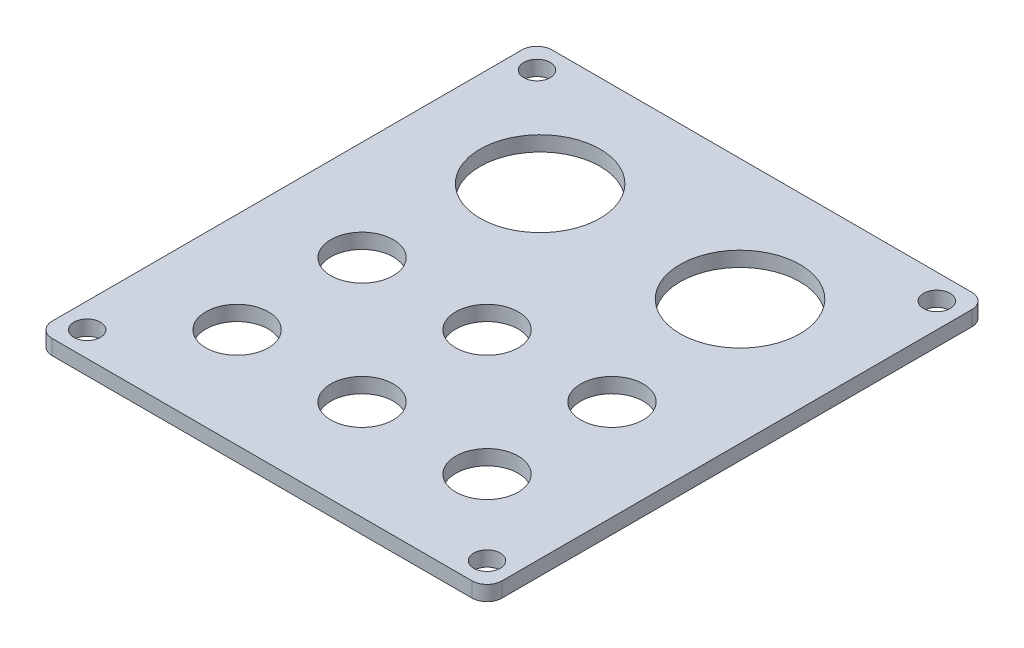
SolidWorks part; units mm, degrees
ref_plane "Front Plane" through (0, 0, 0) normal (0, 0, 1) x (1, 0, 0)
ref_plane "Top Plane" through (0, 0, 0) normal (0, 1, 0) x (1, 0, 0)
ref_plane "Right Plane" through (0, 0, 0) normal (1, 0, 0) x (0, 0, -1)
sketch "Sketch1" plane through (0, 0, 0) normal (0, 1, 0) x (1, 0, 0)
  line L1 (0, 0) -> (90, 0)
  line L2 (0, 0) -> (0, 100)
  line L3 (0, 100) -> (90, 100)
  line L4 (90, 0) -> (90, 100)
  dimension "D1" = 100
  dimension "D2" = 90
extrude "Boss-Extrude1" add sketch "Sketch1" along normal blind 3
sketch "Sketch2" plane through (0, 3, 0) normal (0, 1, 0) x (1, 0, 0)
  line L0 (0, 100) -> (0, 0) construction
  line L1 (0, 0) -> (90, 0) construction
  circle A0 centre (20, 20) radius 6.25
  dimension "D1" = 12.5
  dimension "D2" = 20
  dimension "D3" = 20
extrude "Cut-Extrude1" cut sketch "Sketch2" against normal up to surface (3 mm away) up to face at (45, 0, -50)
pattern_linear "LPattern1" count 3 spacing 25 along (1, 0, 0) count 2 spacing 25 along (0, 0, -1) of "Cut-Extrude1"
sketch "Sketch3" plane through (0, 3, 0) normal (0, 1, 0) x (1, 0, 0)
  line L0 (65, 75.625) -> (25, 75.625) construction
  line L1 (90, 100) -> (0, 100) construction
  line L2 (20, 51.25) -> (20, 100) construction
  circle A0 centre (25, 75.625) radius 12
  circle A1 centre (65, 75.625) radius 12
  circle A2 centre (20, 45) radius 6.25 construction
  circle A3 centre (25, 75.625) radius 14 construction
  circle A4 centre (65, 75.625) radius 14 construction
  point P3 (45, 75.625)
  point P5 (45, 100)
  point P13 (20, 75.625)
  dimension "D1" = 24
  dimension "D3" = 28
  dimension "D2" = 40
extrude "Cut-Extrude2" cut sketch "Sketch3" against normal up to surface (3 mm away) up to face at (45, 0, -26.25)
hole_wizard "M5 Clearance Hole1" positions "Sketch4" profile "Sketch5" hole size "M5" standard "ANSI Metric" end condition up to next
sketch "Sketch4" plane through (0, 3, 0) normal (0, 1, 0) x (1, 0, 0)
  line L18 (5, 95) -> (5, 5)
  line L19 (5, 5) -> (85, 5)
  line L20 (85, 5) -> (85, 95)
  line L21 (85, 95) -> (5, 95)
  line L22 (5, 95) -> (5, 5)
  line L23 (5, 5) -> (85, 5)
  line L24 (85, 5) -> (85, 95)
  line L25 (85, 95) -> (5, 95)
  point P135 (5, 95)
  point P136 (5, 5)
  point P137 (85, 5)
  point P138 (85, 95)
  dimension "D1" = 5
sketch "Sketch5" plane through (5, 3, -95) normal (1, 0, 0) x (0, 0, 1)
  line L0 (0, 0) -> (0, 3)
  line L1 (0, 3) -> (2.65, 3)
  line L2 (2.65, 3) -> (2.65, 0)
  line L5 (2.65, 0) -> (0, 0)
  line L11 (0, -6.35) -> (0, 107.95) construction
  dimension "Thru Hole Dia." = 5.3
  dimension "Thru Hole Depth" = 3
fillet "Fillet1" radius 3 4 edges at (90, 1.5, -100) (90, 1.5, 0) (0, 1.5, 0) (0, 1.5, -100)
